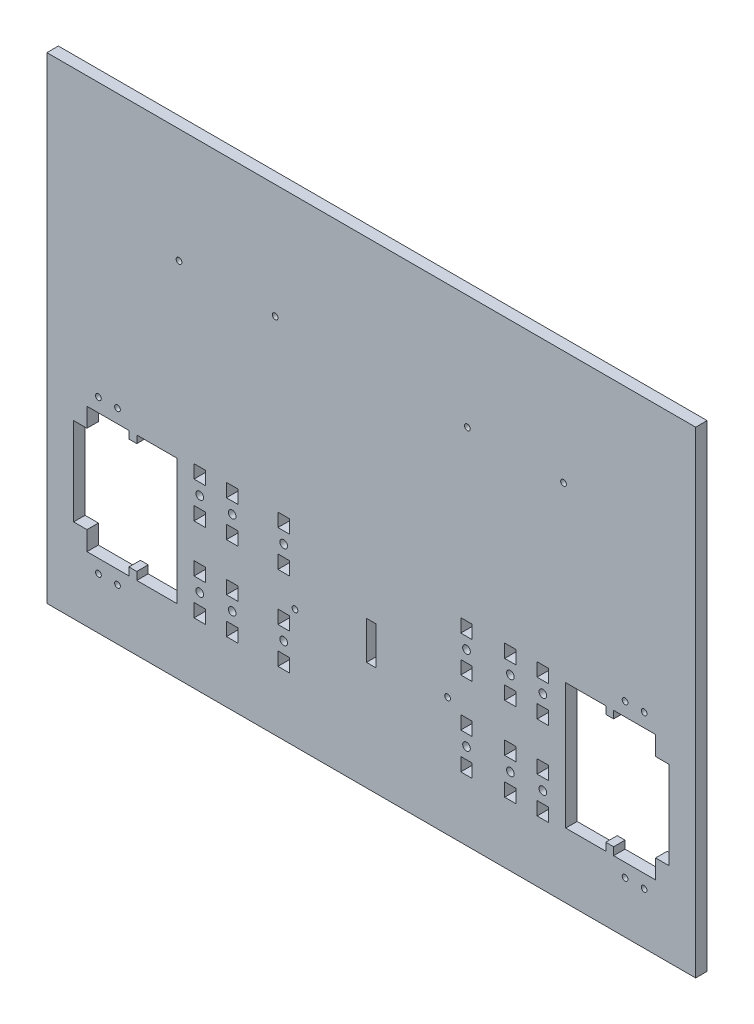
SolidWorks part; units mm, degrees
ref_plane "Plan de face" through (0, 0, 0) normal (0, 0, 1) x (1, 0, 0)
ref_plane "Plan de dessus" through (0, 0, 0) normal (0, 1, 0) x (1, 0, 0)
ref_plane "Plan de droite" through (0, 0, 0) normal (1, 0, 0) x (0, 0, -1)
sketch "Esquisse1" plane through (0, 0, 0) normal (0, 0, 1) x (1, 0, 0)
  line L1 (0, 0) -> (-340, 0)
  line L2 (0, 0) -> (0, 250)
  line L3 (0, 250) -> (-340, 250)
  line L4 (-340, 0) -> (-340, 250)
  line L5 (-340, 0) -> (-340, -49.0561)
  line L6 (0, 0) -> (0, -49.0561)
  point P12 (-170, 0)
  point P13 (-170, 0)
  point P14 (-170, 0)
  dimension "D1" = 340
  dimension "D2" = 250
extrude "Boss.-Extru.1" add sketch "Esquisse1" against normal blind 6
sketch "Esquisse10" plane through (0, 0, -6) normal (0, 0, -1) x (-1, 0, 0)
  line L0 (200.4149, 67) -> (170, 67) construction
  line L1 (170, 67) -> (170, 216.8472) construction
  line L2 (259.9, 58) -> (259.9, 76) construction
  line L3 (262.9, 32) -> (256.9, 32)
  line L4 (262.9, 32) -> (262.9, 39)
  line L5 (262.9, 39) -> (256.9, 39)
  line L6 (256.9, 32) -> (256.9, 39)
  line L7 (262.9, 51) -> (256.9, 51)
  line L8 (262.9, 51) -> (262.9, 58)
  line L9 (262.9, 58) -> (256.9, 58)
  line L10 (256.9, 51) -> (256.9, 58)
  line L11 (262.9, 76) -> (256.9, 76)
  line L12 (262.9, 76) -> (262.9, 83)
  line L13 (262.9, 83) -> (256.9, 83)
  line L14 (256.9, 76) -> (256.9, 83)
  line L15 (262.9, 95) -> (256.9, 95)
  line L16 (262.9, 95) -> (262.9, 102)
  line L17 (262.9, 102) -> (256.9, 102)
  line L18 (256.9, 95) -> (256.9, 102)
  line L19 (245.9, 32) -> (239.9, 32)
  line L20 (172.5, 57) -> (167.5, 57)
  line L21 (172.5, 57) -> (172.5, 77)
  line L22 (172.5, 77) -> (167.5, 77)
  line L23 (167.5, 57) -> (167.5, 77)
  line L24 (245.9, 32) -> (245.9, 39)
  line L25 (245.9, 39) -> (239.9, 39)
  line L26 (239.9, 32) -> (239.9, 39)
  line L27 (245.9, 51) -> (239.9, 51)
  line L28 (245.9, 51) -> (245.9, 58)
  line L29 (245.9, 58) -> (239.9, 58)
  line L30 (239.9, 51) -> (239.9, 58)
  line L31 (245.9, 76) -> (239.9, 76)
  line L32 (245.9, 76) -> (245.9, 83)
  line L33 (245.9, 83) -> (239.9, 83)
  line L34 (239.9, 76) -> (239.9, 83)
  line L35 (245.9, 95) -> (239.9, 95)
  line L36 (245.9, 95) -> (245.9, 102)
  line L37 (245.9, 102) -> (239.9, 102)
  line L38 (239.9, 95) -> (239.9, 102)
  line L39 (215.0613, 88.0489) -> (215.0613, 106.0489) construction
  line L40 (242.9, 58) -> (242.9, 76) construction
  line L41 (242.9, 39) -> (242.9, 51) construction
  line L42 (242.9, 83) -> (242.9, 95) construction
  line L43 (218.9, 32) -> (212.9, 32)
  line L44 (218.9, 32) -> (218.9, 39)
  line L45 (218.9, 39) -> (212.9, 39)
  line L46 (212.9, 32) -> (212.9, 39)
  line L47 (218.9, 51) -> (212.9, 51)
  line L48 (218.9, 51) -> (218.9, 58)
  line L49 (218.9, 58) -> (212.9, 58)
  line L50 (212.9, 51) -> (212.9, 58)
  line L51 (218.9, 76) -> (212.9, 76)
  line L52 (218.9, 76) -> (218.9, 83)
  line L53 (218.9, 83) -> (212.9, 83)
  line L54 (212.9, 76) -> (212.9, 83)
  line L55 (218.9, 95) -> (212.9, 95)
  line L56 (188.0613, 88.0489) -> (188.0613, 106.0489) construction
  line L57 (259.9, 39) -> (259.9, 51) construction
  line L58 (259.9, 83) -> (259.9, 95) construction
  line L59 (100.1, 95) -> (100.1, 102)
  line L60 (94.1, 102) -> (100.1, 102)
  line L61 (94.1, 95) -> (94.1, 102)
  line L62 (94.1, 95) -> (100.1, 95)
  line L63 (100.1, 76) -> (100.1, 83)
  line L64 (94.1, 83) -> (100.1, 83)
  line L65 (94.1, 76) -> (94.1, 83)
  line L66 (94.1, 76) -> (100.1, 76)
  line L67 (100.1, 51) -> (100.1, 58)
  line L68 (94.1, 58) -> (100.1, 58)
  line L69 (94.1, 51) -> (94.1, 58)
  line L70 (94.1, 51) -> (100.1, 51)
  line L71 (100.1, 32) -> (100.1, 39)
  line L72 (94.1, 39) -> (100.1, 39)
  line L73 (94.1, 32) -> (94.1, 39)
  line L74 (94.1, 32) -> (100.1, 32)
  line L75 (83.1, 95) -> (83.1, 102)
  line L76 (77.1, 102) -> (83.1, 102)
  line L77 (77.1, 95) -> (77.1, 102)
  line L78 (77.1, 95) -> (83.1, 95)
  line L79 (83.1, 76) -> (83.1, 83)
  line L80 (77.1, 83) -> (83.1, 83)
  line L81 (77.1, 76) -> (77.1, 83)
  line L82 (77.1, 76) -> (83.1, 76)
  line L83 (187, 67) -> (17, 67) construction
  line L84 (123.1, 95) -> (123.1, 102)
  line L85 (117.1, 102) -> (123.1, 102)
  line L86 (117.1, 95) -> (117.1, 102)
  line L87 (117.1, 95) -> (123.1, 95)
  line L88 (123.1, 76) -> (123.1, 83)
  line L89 (117.1, 83) -> (123.1, 83)
  line L90 (117.1, 76) -> (117.1, 83)
  line L91 (83.1, 51) -> (83.1, 58)
  line L92 (77.1, 58) -> (83.1, 58)
  line L93 (77.1, 51) -> (77.1, 58)
  line L94 (77.1, 51) -> (83.1, 51)
  line L95 (117.1, 76) -> (123.1, 76)
  line L96 (123.1, 51) -> (123.1, 58)
  line L97 (117.1, 58) -> (123.1, 58)
  line L98 (117.1, 51) -> (117.1, 58)
  line L99 (117.1, 51) -> (123.1, 51)
  line L100 (123.1, 32) -> (123.1, 39)
  line L101 (117.1, 39) -> (123.1, 39)
  line L102 (117.1, 32) -> (117.1, 39)
  line L103 (83.1, 32) -> (83.1, 39)
  line L104 (77.1, 39) -> (83.1, 39)
  line L105 (77.1, 32) -> (77.1, 39)
  line L106 (77.1, 32) -> (83.1, 32)
  line L107 (170, 67) -> (0, 67) construction
  line L108 (271.9, 34) -> (292.9, 34)
  line L109 (271.9, 34) -> (271.9, 100)
  line L110 (271.9, 100) -> (292.9, 100)
  line L111 (292.9, 34) -> (292.9, 100)
  line L112 (68.1, 34) -> (47.1, 34)
  line L113 (68.1, 34) -> (68.1, 100)
  line L114 (68.1, 100) -> (47.1, 100)
  line L115 (47.1, 34) -> (47.1, 100)
  line L116 (0, 250) -> (340, 250) construction
  line L117 (0, -49.0561) -> (0, 200) construction
  line L118 (47.1, 67) -> (0, 67) construction
  line L119 (292.9, 67) -> (340, 67) construction
  line L121 (117.1, 32) -> (123.1, 32)
  line L122 (210, 67) -> (40, 67) construction
  line L123 (218.9, 95) -> (218.9, 102)
  line L124 (218.9, 102) -> (212.9, 102)
  line L125 (212.9, 95) -> (212.9, 102)
  line L126 (215.9, 58) -> (215.9, 76) construction
  line L127 (215.9, 39) -> (215.9, 51) construction
  line L128 (215.9, 83) -> (215.9, 95) construction
  line L130 (340, 0) -> (340, 250) construction
  circle A0 centre (259.9, 45) radius 2
  circle A1 centre (259.9, 89) radius 2
  circle A2 centre (242.9, 45) radius 2
  circle A3 centre (242.9, 89) radius 2
  circle A4 centre (215.9, 45) radius 2
  circle A5 centre (215.9, 89) radius 2
  circle A6 centre (97.1, 89) radius 2
  circle A7 centre (97.1, 45) radius 2
  circle A8 centre (80.1, 89) radius 2
  circle A9 centre (120.1, 89) radius 2
  circle A10 centre (120.1, 45) radius 2
  circle A11 centre (80.1, 45) radius 2
  point P21 (259.9, 67)
  point P48 (242.9, 67)
  point P144 (292.9, 67)
  point P150 (68.1, 67)
  point P169 (215.9, 67)
  dimension "D14" = 4
  dimension "D15" = 4
  dimension "D1" = 70
  dimension "D2" = 12
  dimension "D3" = 7
  dimension "D4" = 7
  dimension "D5" = 12
  dimension "D6" = 7
  dimension "D7" = 7
  dimension "D8" = 86.9
  dimension "D9" = 6
  dimension "D10" = 2.5
  dimension "D11" = 2.5
  dimension "D12" = 20
  dimension "D13" = 10
  dimension "D16" = 9
  dimension "D17" = 21
  dimension "D18" = 66
  dimension "D19" = 66
  dimension "D20" = 9
  dimension "D21" = 21
  dimension "D22" = 150
  dimension "D23" = 2
  dimension "D27" = 11
  dimension "D28" = 34
  dimension "D29" = 11
  dimension "D30" = 38
  dimension "D24" = 2
  dimension "D25" = 2
  dimension "D26" = 2
extrude "Enlèv. mat.-Extru.5" cut sketch "Esquisse10" against normal blind 6
sketch "Esquisse13" plane through (0, 0, -6) normal (0, 0, -1) x (-1, 0, 0)
  line L0 (43, 100) -> (21, 100)
  line L1 (43, 100) -> (43, 96.0745)
  line L2 (43, 34) -> (21, 34)
  line L3 (14, 90) -> (14, 44)
  line L4 (170, 197.2117) -> (170, 30) construction
  line L5 (31.2729, 67.0745) -> (52.2729, 67.0745) construction
  line L6 (297, 38.0745) -> (297, 34)
  line L7 (292.9, 96.0745) -> (292.9, 38.0745)
  line L8 (297, 38.0745) -> (292.9, 38.0745)
  line L9 (297, 96.0745) -> (292.9, 96.0745)
  line L10 (-4.3481, 139.0454) -> (14.1729, 131.4974) construction
  line L11 (56.9221, 195.6452) -> (82.0234, 184.3851) construction
  line L12 (69.2498, 190.1152) -> (170, 190.1152) construction
  line L13 (319, 34) -> (319, 44)
  line L14 (326, 44) -> (319, 44)
  line L15 (319, 100) -> (319, 90)
  line L16 (14, 90) -> (21, 90)
  line L17 (21, 100) -> (21, 90)
  line L18 (326, 90) -> (319, 90)
  line L19 (14, 44) -> (21, 44)
  line L20 (21, 34) -> (21, 44)
  line L21 (43, 96.0745) -> (47.1, 96.0745)
  line L22 (43, 38.0745) -> (47.1, 38.0745)
  line L23 (47.1, 96.0745) -> (47.1, 38.0745)
  line L24 (43, 38.0745) -> (43, 34)
  line L25 (326, 90) -> (326, 44)
  line L26 (297, 34) -> (319, 34)
  line L27 (297, 100) -> (297, 96.0745)
  line L28 (297, 100) -> (319, 100)
  line L29 (32, 34) -> (32, 27) construction
  line L30 (27, 34) -> (37, 34) construction
  line L31 (27, 34) -> (27, 27) construction
  line L32 (27, 27) -> (37, 27) construction
  line L33 (37, 34) -> (37, 27) construction
  line L34 (68.1, 34) -> (68.1, 100) construction
  line L36 (68.1, 100) -> (47.1, 100) construction
  line L37 (47.1, 100) -> (47.1, 34) construction
  line L38 (0, 0) -> (340, 0) construction
  circle A1 centre (69.2498, 190.1152) radius 1.5
  circle A2 centre (119.6249, 190.1152) radius 1.5
  circle A3 centre (220.3751, 190.1152) radius 1.5
  circle A4 centre (270.7502, 190.1152) radius 1.5
  circle A5 centre (27, 27) radius 1.5
  circle A6 centre (130, 62.4) radius 1.5
  circle A7 centre (210, 62.4) radius 1.5
  circle A8 centre (37, 27) radius 1.5
  circle A9 centre (37, 107.1489) radius 1.5
  circle A10 centre (27, 107.1489) radius 1.5
  circle A11 centre (303, 27) radius 1.5
  circle A12 centre (313, 27) radius 1.5
  circle A13 centre (313, 107.1489) radius 1.5
  circle A14 centre (303, 107.1489) radius 1.5
  point P67 (68.1, 67)
  point P68 (14, 67)
  dimension "D3" = 3
  dimension "D6" = 3
  dimension "D7" = 3
  dimension "D16" = 3
  dimension "D17" = 3
  dimension "D1" = 66
  dimension "D4" = 3.9255
  dimension "D5" = 14
  dimension "D8" = 40
  dimension "D9" = 32.4
  dimension "D10" = 7
  dimension "D11" = 10
  dimension "D12" = 10
  dimension "D13" = 22
  dimension "D14" = 7
  dimension "D15" = 10
  dimension "D18" = 33.1
  dimension "D19" = 4.0745
  dimension "D20" = 22.1498
  dimension "D21" = 82.9
  dimension "D22" = 7.1489
  dimension "D23" = 30
extrude "Enlèv. mat.-Extru.6" cut sketch "Esquisse13" against normal blind 6
